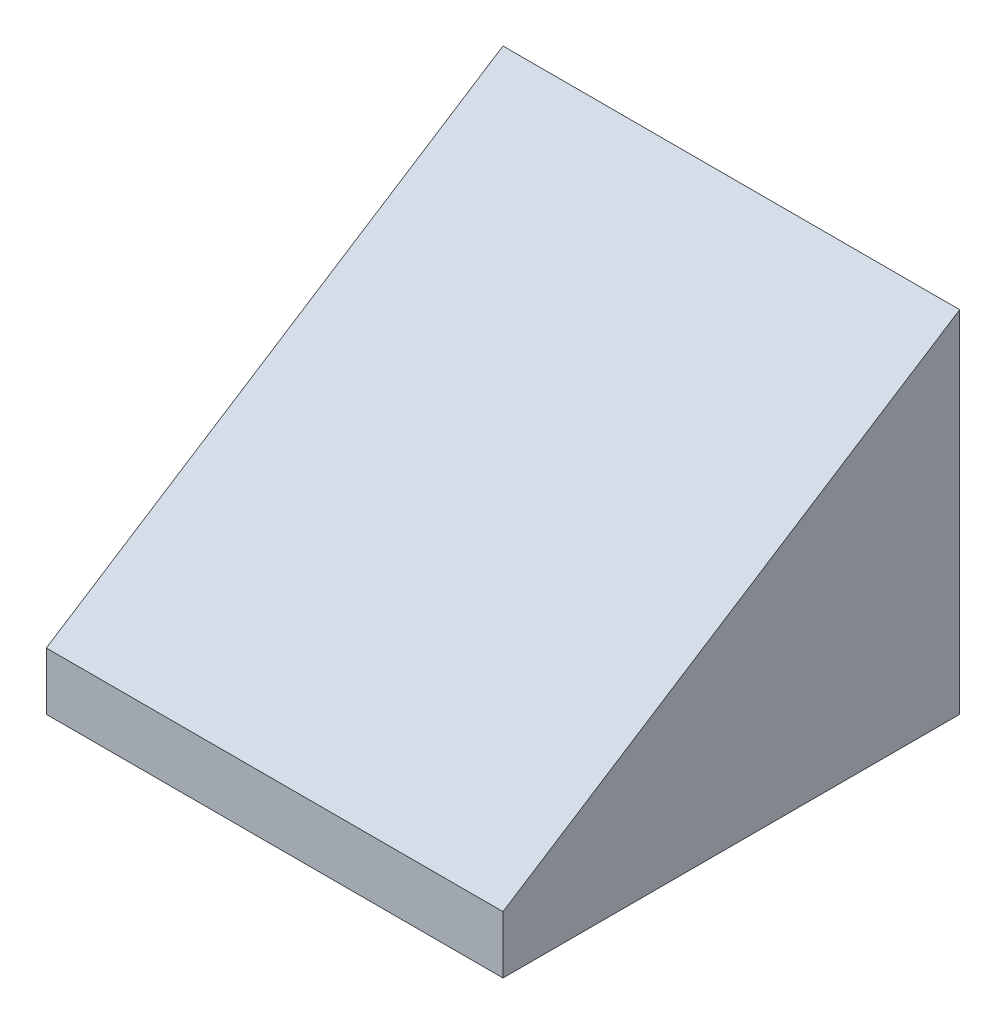
SolidWorks part; units mm, degrees
ref_plane "Front Plane" through (0, 0, 0) normal (0, 0, 1) x (1, 0, 0)
ref_plane "Top Plane" through (0, 0, 0) normal (0, 1, 0) x (1, 0, 0)
ref_plane "Right Plane" through (0, 0, 0) normal (1, 0, 0) x (0, 0, -1)
sketch "Sketch1" plane through (0, 0, 0) normal (1, 0, 0) x (0, 0, -1)
  line L1 (0, 0) -> (7.95, 0)
  line L2 (0, 0) -> (0, -6.1)
  line L3 (0, -6.1) -> (7.95, -6.1)
  line L4 (7.95, 0) -> (7.95, -6.1)
  dimension "D1" = 7.95
  dimension "D2" = 6.1
extrude "Boss-Extrude1" add sketch "Sketch1" against normal blind 7.95
sketch "Sketch2" plane through (0, 0, 0) normal (1, 0, 0) x (0, 0, -1)
  line L0 (7.95, 0) -> (0, -5.1)
  line L1 (0, 0) -> (0, -6.1) construction
  line L2 (0, -5.1) -> (0, 0)
  line L3 (0, 0) -> (7.95, 0)
  dimension "D1" = 1
extrude "Cut-Extrude1" cut sketch "Sketch2" against normal blind 17.7
sketch "Sketch3" plane through (0, -6.1, 0) normal (0, -1, 0) x (1, 0, 0)
  line L0 (-3.975, 0) -> (-3.975, -7.95) construction
  line L1 (-7.95, 0) -> (0, 0) construction
  line L2 (-7.95, -7.95) -> (0, -7.95) construction
  line L3 (-3.975, -7.95) -> (0, -3.975) construction
  line L4 (0, 0) -> (0, -7.95) construction
  line L5 (0, -3.975) -> (-7.95, -3.975) construction
  line L6 (-7.95, 0) -> (-7.95, -7.95) construction
  line L8 (-6.45, -1.5) -> (-1.5, -1.5)
  line L9 (-6.45, -1.5) -> (-6.45, -6.45)
  line L10 (-6.45, -6.45) -> (-1.5, -6.45)
  line L11 (-1.5, -1.5) -> (-1.5, -6.45)
  line L12 (-6.45, -1.5) -> (-1.5, -6.45) construction
  line L13 (-6.45, -6.45) -> (-1.5, -1.5) construction
  point P6 (-3.975, -3.975)
  dimension "D1" = 1.5
  dimension "D2" = 1.5
extrude "Cut-Extrude2" cut sketch "Sketch3" against normal blind 1.7
